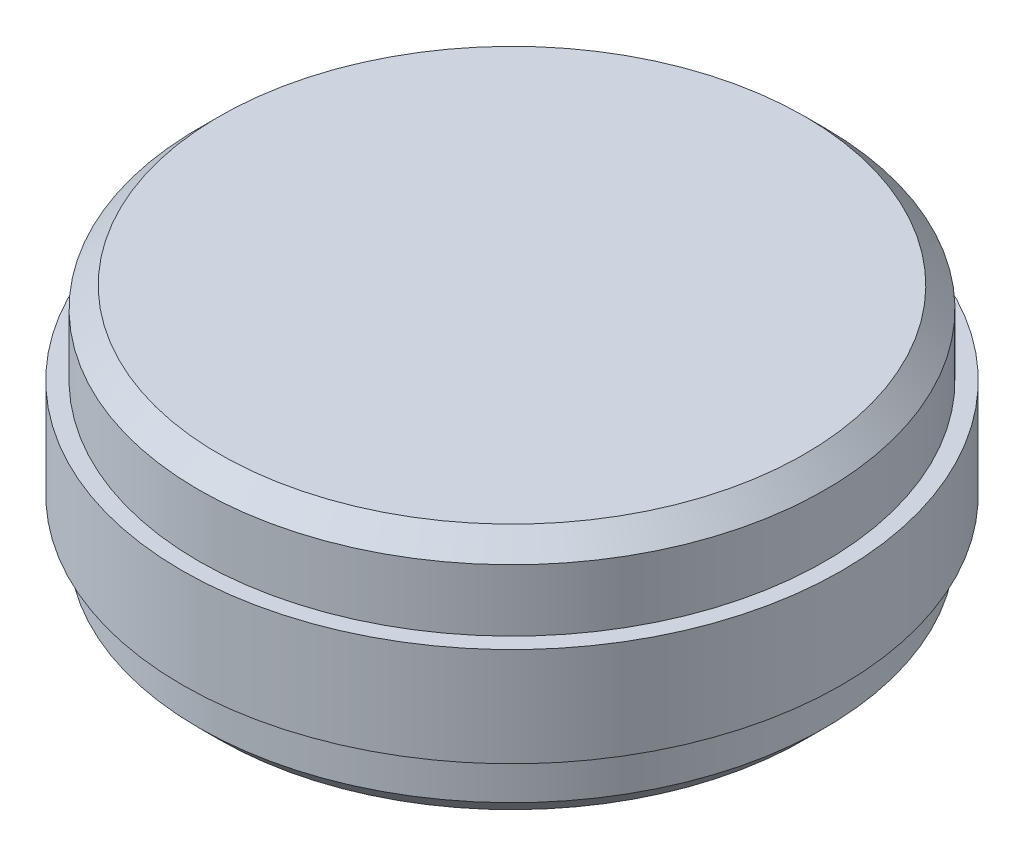
SolidWorks part; units mm, degrees
material "6061 Alloy"
ref_plane "Front Plane" through (0, 0, 0) normal (0, 0, 1) x (1, 0, 0)
ref_plane "Top Plane" through (0, 0, 0) normal (0, 1, 0) x (1, 0, 0)
ref_plane "Right Plane" through (0, 0, 0) normal (1, 0, 0) x (0, 0, -1)
sketch "Sketch1" plane through (0, 0, 0) normal (0, 0, 1) x (1, 0, 0)
  line L0 (0, 0) -> (0, -84.5335) construction
  line L1 (0, 0) -> (24.13, 0)
  line L2 (24.13, 0) -> (24.13, -6.35)
  line L3 (24.13, -6.35) -> (25.4, -6.35)
  line L4 (25.4, -6.35) -> (25.4, -13.97)
  line L5 (25.4, -13.97) -> (24.13, -13.97)
  line L6 (24.13, -13.97) -> (24.13, -19.05)
  line L7 (24.13, -19.05) -> (0, -19.05)
  line L8 (0, -19.05) -> (0, 0)
  point P3 (0, 0)
  point P11 (0, 0)
  point P12 (0, 0)
  dimension "D1" = 50.8
  dimension "D2" = 48.26
  dimension "D3" = 5.08
  dimension "D4" = 6.35
  dimension "D5" = 19.05
revolve "Revolve1" add sketch "Sketch1" angle 360 about L0
chamfer "lox install" distance 1.5875 angle 45 1 edges at (0, 0, 24.13)
chamfer "o-ring install" distance 1.5875 angle 45 1 edges at (0, -19.05, 24.13)
